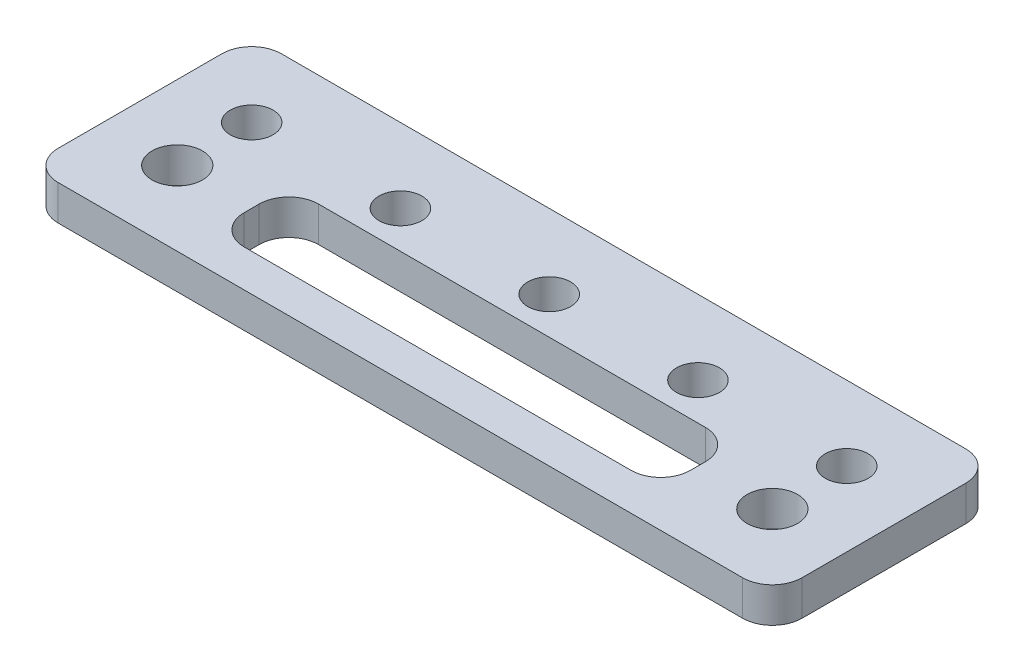
SolidWorks part; units mm, degrees
material "Custom Plastic"
ref_plane "Front Plane" through (0, 0, 0) normal (0, 0, 1) x (1, 0, 0)
ref_plane "Top Plane" through (0, 0, 0) normal (0, 1, 0) x (1, 0, 0)
ref_plane "Right Plane" through (0, 0, 0) normal (1, 0, 0) x (0, 0, -1)
sketch "Sketch1" plane through (0, 0, 0) normal (0, 1, 0) x (1, 0, 0)
  line L1 (31.75, -9.525) -> (-31.75, -9.525)
  line L2 (31.75, -9.525) -> (31.75, 9.525)
  line L3 (31.75, 9.525) -> (-31.75, 9.525)
  line L4 (-31.75, -9.525) -> (-31.75, 9.525)
  line L5 (31.75, -9.525) -> (-31.75, 9.525) construction
  line L6 (31.75, 9.525) -> (-31.75, -9.525) construction
  point P0 (0, 0)
  dimension "D1" = 63.5
  dimension "D2" = 19.05
extrude "Boss-Extrude1" add sketch "Sketch1" along normal blind 3
sketch "Sketch2" plane through (0, 3, 0) normal (0, 1, 0) x (1, 0, 0)
  line L0 (0, -3.175) -> (-12.7, -3.175) construction
  line L1 (-12.7, -3.175) -> (-25.4, -3.175) construction
  line L2 (0, -3.175) -> (12.7, -3.175) construction
  line L3 (12.7, -3.175) -> (25.4, -3.175) construction
  line L4 (0, -3.175) -> (0, 3.175) construction
  line L6 (25.4, -3.175) -> (25.4, 3.175) construction
  line L7 (-31.75, -9.525) -> (31.75, -9.525) construction
  line L8 (-25.4, -3.175) -> (-25.4, 3.175) construction
  line L9 (-25.4, 3.175) -> (0, 3.175) construction
  line L10 (0, 3.175) -> (25.4, 3.175) construction
  point P11 (-12.7, 3.175)
  point P13 (12.7, 3.175)
  dimension "D1" = 12.7
  dimension "D2" = 6.35
  dimension "D3" = 6.35
hole_wizard "#6 Clearance Hole1" positions "Sketch4" profile "Sketch5" hole size "#6" standard "ANSI Inch" end condition through all
sketch "Sketch4" plane through (0, 3, 0) normal (0, 1, 0) x (1, 0, 0)
  point P15 (-25.4, 3.175)
  point P18 (0, 3.175)
  point P21 (25.4, 3.175)
  point P25 (12.7, 3.175)
  point P27 (-12.7, 3.175)
sketch "Sketch5" plane through (-25.4, 3, -3.175) normal (1, 0, 0) x (0, 0, 1)
  line L0 (0, 0) -> (0, 3)
  line L1 (0, 3) -> (1.8288, 3)
  line L2 (1.8288, 3) -> (1.8288, 0)
  line L5 (1.8288, 0) -> (0, 0)
  line L11 (0, -6.35) -> (0, 107.95) construction
  dimension "Thru Hole Dia." = 3.6576
  dimension "Thru Hole Depth" = 3
hole_wizard "#8 Clearance Hole1" positions "Sketch7" profile "Sketch6" hole size "#8" standard "ANSI Inch" end condition through all
sketch "Sketch7" plane through (0, 3, 0) normal (0, 1, 0) x (1, 0, 0)
  point P0 (-25.4, -3.175)
  point P3 (25.4, -3.175)
sketch "Sketch6" plane through (-25.4, 3, 3.175) normal (1, 0, 0) x (0, 0, 1)
  line L0 (0, 0) -> (0, 3)
  line L1 (0, 3) -> (2.1526, 3)
  line L2 (2.1526, 3) -> (2.1526, 0)
  line L5 (2.1526, 0) -> (0, 0)
  line L11 (0, -6.35) -> (0, 107.95) construction
  dimension "Thru Hole Dia." = 4.3053
  dimension "Thru Hole Depth" = 3
fillet "Fillet1" radius 2.54 4 edges at (31.75, 1.5, 9.525) (31.75, 1.5, -9.525) (-31.75, 1.5, 9.525) (-31.75, 1.5, -9.525)
sketch "Sketch8" plane through (0, 3, 0) normal (0, 1, 0) x (1, 0, 0)
  line L0 (-29.21, -9.525) -> (29.21, -9.525) construction
  line L1 (16.51, -6.35) -> (-16.51, -6.35)
  line L2 (19.05, -3.81) -> (19.05, -2.54)
  line L3 (16.51, 0) -> (-16.51, 0)
  line L4 (-19.05, -3.81) -> (-19.05, -2.54)
  line L5 (19.05, -6.35) -> (-19.05, 0) construction
  line L6 (19.05, 0) -> (-19.05, -6.35) construction
  circle A0 centre (0, 3.175) radius 1.8288 construction
  circle A1 centre (25.4, -3.175) radius 2.1526 construction
  arc A2 (19.05, -2.54) -> (16.51, 0) centre (16.51, -2.54) ccw
  arc A3 (16.51, -6.35) -> (19.05, -3.81) centre (16.51, -3.81) ccw
  arc A4 (-16.51, -6.35) -> (-19.05, -3.81) centre (-16.51, -3.81) cw
  arc A5 (-16.51, 0) -> (-19.05, -2.54) centre (-16.51, -2.54) ccw
  point P0 (0, -3.175)
  dimension "D2" = 3.175
  dimension "D4" = 2.54
  dimension "D1" = 3.175
  dimension "D3" = 6.35
extrude "Cut-Extrude1" cut sketch "Sketch8" against normal through all
